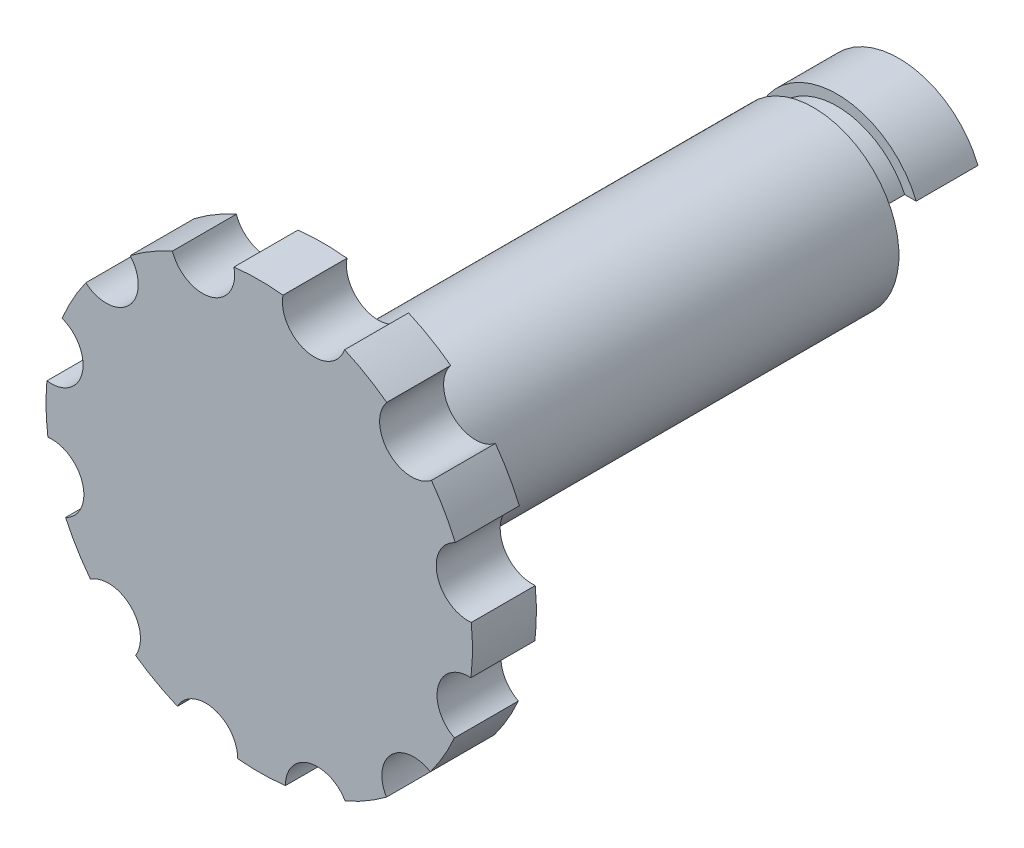
SolidWorks part; units mm, degrees
material "6061-T6 (SS)"
ref_plane "Front Plane" through (0, 0, 0) normal (0, 0, 1) x (1, 0, 0)
ref_plane "Top Plane" through (0, 0, 0) normal (0, 1, 0) x (1, 0, 0)
ref_plane "Right Plane" through (0, 0, 0) normal (1, 0, 0) x (0, 0, -1)
sketch "Sketch2" plane through (0, 0, 0) normal (0, 0, 1) x (1, 0, 0)
  circle A0 centre (0, 0) radius 10
  dimension "D1" = 20
extrude "Boss-Extrude1" add sketch "Sketch2" along normal blind 8
sketch "Sketch3" plane through (0, 0, 0) normal (0, 0, -1) x (-1, 0, 0)
  circle A0 centre (0, 0) radius 4
  dimension "D1" = 8
extrude "Boss-Extrude2" add sketch "Sketch3" along normal blind 18
sketch "Sketch4" plane through (0, 0, -18) normal (0, 0, -1) x (-1, 0, 0)
  line L0 (3.7081, 1.5) -> (-3.7081, 1.5)
  circle A0 centre (0, 0) radius 4 construction
  circle A1 centre (0, 0) radius 4 construction
  circle A2 centre (0, 0) radius 4
  circle M2 centre (0, 0) radius 4
  dimension "D2" = 8
  dimension "D1" = 1.5
extrude "Boss-Extrude3" add sketch "Sketch4" along normal blind 4 contours L0 M2
sketch "Sketch5" plane through (0, 0, 8) normal (0, 0, 1) x (1, 0, 0)
  line L0 (2.5882, 9.6593) -> (0, 0) construction
  line L1 (0, 0) -> (0, 10) construction
  circle A4 centre (2.5882, 9.6593) radius 1.5
  circle A13 centre (0, 0) radius 10 construction
  circle A14 centre (7.1467, 7.0716) radius 1.5
  circle A15 centre (9.8007, 2.5514) radius 1.5
  circle A16 centre (9.839, -2.6902) radius 1.5
  circle A17 centre (7.2513, -7.2487) radius 1.5
  circle A18 centre (2.7311, -9.9027) radius 1.5
  circle A19 centre (-2.5105, -9.941) radius 1.5
  circle A20 centre (-7.069, -7.3534) radius 1.5
  circle A21 centre (-9.723, -2.8331) radius 1.5
  circle A22 centre (-9.7613, 2.4085) radius 1.5
  circle A23 centre (-7.1736, 6.967) radius 1.5
  circle A24 centre (-2.6534, 9.621) radius 1.5
  dimension "D1" = 165
  dimension "D3" = 3
  dimension "D2" = 12
extrude "Cut-Extrude1" cut sketch "Sketch5" against normal through all
sketch "Sketch7" plane through (0, 0, 0) normal (0, 0, -1) x (-1, 0, 0)
  line L0 (0, 7) -> (0, 0) construction
  line L1 (0, 0) -> (4.015, 5.7341) construction
  line L2 (4.015, 5.7341) -> (-4.015, 5.7341) construction
  circle A0 centre (0, 0) radius 7
  circle A2 centre (0, 7) radius 1.5
  dimension "D1" = 14
  dimension "D4" = 3
  dimension "D2" = 145
extrude "Cut-Extrude4" cut sketch "Sketch7" against normal blind 5
sketch "Sketch8" plane through (0, 0, 0) normal (0, 1, 0) x (1, 0, 0)
  line L1 (-5.5081, 19.1) -> (-3.5081, 19.1)
  line L2 (-5.5081, 19.1) -> (-5.5081, 18)
  line L3 (-5.5081, 18) -> (-3.5081, 18)
  line L4 (-3.5081, 19.1) -> (-3.5081, 18)
  line L5 (-3.7081, 22) -> (-3.7081, 18) construction
  line L6 (4, 18) -> (-4, 18) construction
  line L7 (0, 0) -> (0, 41.0029) construction
  dimension "D1" = 0.2
  dimension "D2" = 1.1
  dimension "D3" = 2
  dimension "D4" = 0
revolve "Cut-Revolve2" cut sketch "Sketch8" angle 360 about L7
equation "\"360.00degז\"=360"
equation "\"זזזזז\"=360"
equation "\"ז\"=360"
equation "\"זזזז\"=10"
equation "\"זז\"=360"
